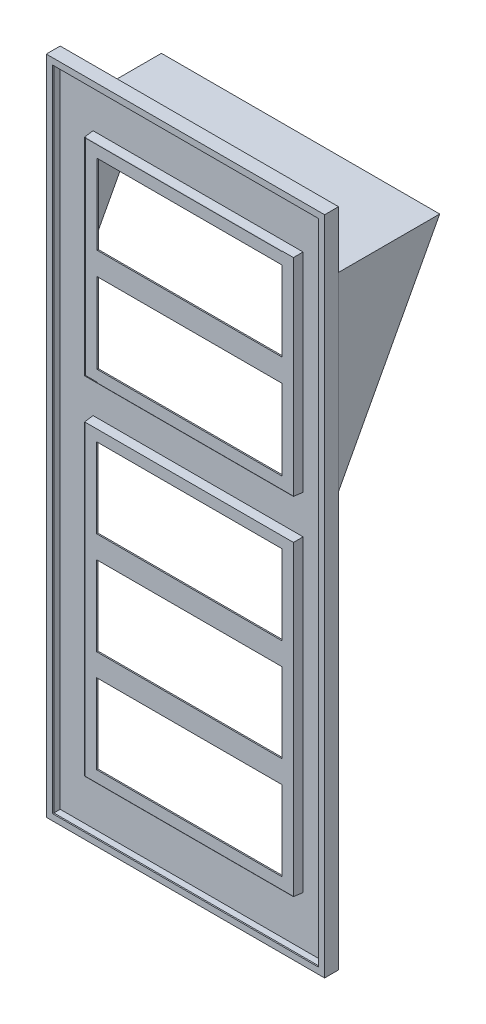
SolidWorks part; units mm, degrees
ref_plane "정면" through (0, 0, 0) normal (0, 0, 1) x (1, 0, 0)
ref_plane "윗면" through (0, 0, 0) normal (0, 1, 0) x (1, 0, 0)
ref_plane "우측면" through (0, 0, 0) normal (1, 0, 0) x (0, 0, -1)
sketch "스케치1" plane through (0, 0, 0) normal (0, 0, 1) x (1, 0, 0)
  line L1 (0, 0) -> (44, 0)
  line L2 (0, 0) -> (0, 104.5)
  line L3 (0, 104.5) -> (44, 104.5)
  line L4 (44, 0) -> (44, 104.5)
  dimension "D1" = 104.5
  dimension "D2" = 44
extrude "보스-돌출1" add sketch "스케치1" along normal blind 2
shell "쉘1" thickness 0.2
sketch "스케치2" plane through (0, 0, 0.2) normal (0, 0, 1) x (1, 0, 0)
  line L0 (44, 104.5) -> (0, 104.5) construction
  line L1 (5.6, 95.5) -> (38.4, 95.5)
  line L2 (5.6, 95.5) -> (5.6, 63)
  line L3 (5.6, 63) -> (38.4, 63)
  line L4 (38.4, 95.5) -> (38.4, 63)
  line L5 (5.6, 56.5) -> (38.4, 56.5)
  line L6 (5.6, 56.5) -> (5.6, 8.2)
  line L7 (5.6, 8.2) -> (38.4, 8.2)
  line L8 (38.4, 56.5) -> (38.4, 8.2)
  line L9 (0.2, 0.2) -> (43.8, 0.2) construction
  line L12 (0, 104.5) -> (0, 0) construction
  point P14 (22, 95.5)
  point P15 (22, 56.5)
  dimension "D1" = 9
  dimension "D2" = 32.5
  dimension "D3" = 6.5
  dimension "D4" = 8
  dimension "D5" = 32.8
  dimension "D6" = 32.8
  dimension "D7" = 22
  dimension "D8" = 22
extrude "컷-돌출1" cut sketch "스케치2" against normal blind 2
sketch "스케치3" plane through (0, 0, 0.2) normal (0, 0, 1) x (1, 0, 0)
  line L0 (5.6, 8.2) -> (38.4, 8.2) construction
  line L1 (5.6, 56.5) -> (5.6, 8.2) construction
  line L2 (38.4, 56.5) -> (5.6, 56.5) construction
  line L3 (38.4, 8.2) -> (38.4, 56.5) construction
  line L4 (5.6, 63) -> (38.4, 63)
  line L5 (5.6, 95.5) -> (5.6, 63)
  line L6 (38.4, 95.5) -> (5.6, 95.5)
  line L7 (38.4, 63) -> (38.4, 95.5)
  line L8 (5.6, 63) -> (38.4, 63)
  line L9 (5.6, 95.5) -> (5.6, 63)
  line L10 (38.4, 95.5) -> (5.6, 95.5)
  line L11 (38.4, 63) -> (38.4, 95.5)
  line L12 (5.6, 8.2) -> (38.4, 8.2)
  line L13 (5.6, 56.5) -> (5.6, 8.2)
  line L14 (38.4, 56.5) -> (5.6, 56.5)
  line L15 (38.4, 8.2) -> (38.4, 56.5)
  line L16 (5.4, 62.8) -> (38.6, 62.8)
  line L17 (38.6, 62.8) -> (38.6, 95.7)
  line L18 (38.6, 95.7) -> (5.4, 95.7)
  line L19 (5.4, 95.7) -> (5.4, 62.8)
  line L20 (5.4, 8) -> (38.6, 8)
  line L21 (38.6, 8) -> (38.6, 56.7)
  line L22 (38.6, 56.7) -> (5.4, 56.7)
  line L23 (5.4, 56.7) -> (5.4, 8)
  dimension "D1" = 0
  dimension "D2" = 0.2
extrude "보스-돌출2" add sketch "스케치3" along normal blind 1.8 draft 4
ref_plane "평면1" through (38.5, 95.6, 1.6301) normal (0, 1, 0) x (1, 0, 0)
ref_plane "평면2" through (0, 0, 1.4) normal (0, 0, 1) x (1, 0, 0)
sketch "스케치6" plane through (0, 0, 1.4) normal (0, 0, 1) x (1, 0, 0)
  line L0 (5.6, 63) -> (38.4, 63) construction
  line L1 (5.6, 95.5) -> (7.45, 95.5)
  line L2 (5.6, 95.5) -> (5.6, 63)
  line L3 (5.6, 63) -> (7.45, 63)
  line L4 (7.45, 95.5) -> (7.45, 63)
  line L6 (7.45, 64.75) -> (38.5, 64.75)
  line L7 (7.45, 64.75) -> (7.45, 62.9)
  line L8 (7.45, 62.9) -> (38.5, 62.9)
  line L9 (38.5, 64.75) -> (38.5, 62.9)
  line L11 (36.65, 64.75) -> (38.5, 64.75)
  line L12 (36.65, 64.75) -> (36.65, 95.6)
  line L13 (36.65, 95.6) -> (38.5, 95.6)
  line L14 (38.5, 64.75) -> (38.5, 95.6)
  line L15 (47.4925, 95.6) -> (29.5075, 95.6) construction
  line L16 (36.65, 93.65) -> (7.45, 93.65)
  line L17 (36.65, 93.65) -> (36.65, 95.5)
  line L18 (36.65, 95.5) -> (7.45, 95.5)
  line L19 (7.45, 93.65) -> (7.45, 95.5)
  line L20 (36.65, 77.45) -> (7.45, 77.45)
  line L21 (36.65, 77.45) -> (36.65, 81.05)
  line L22 (36.65, 81.05) -> (7.45, 81.05)
  line L23 (7.45, 77.45) -> (7.45, 81.05)
  line L24 (38.5, 62.9) -> (38.5, 95.6) construction
  dimension "D1" = 1.85
  dimension "D2" = 1.85
  dimension "D3" = 1.85
  dimension "D4" = 1.85
  dimension "D5" = 3.6
  dimension "D6" = 12.6
extrude "보스-돌출3" add sketch "스케치6" along normal blind 0.2 separate body contours L4 L1 L2 L3 | L9 L6 L4 L8 | L6 L14 L13 L12 | L12 L22 L4 L20 | L12 L18 L4 L16
sketch "스케치7" plane through (0, 0, 1.4) normal (0, 0, 1) x (1, 0, 0)
  line L1 (5.5, 56.6) -> (38.5, 56.6)
  line L2 (5.5, 56.6) -> (5.5, 8.1)
  line L3 (5.5, 8.1) -> (38.5, 8.1)
  line L4 (38.5, 56.6) -> (38.5, 8.1)
  line L5 (7.35, 22.5) -> (36.65, 22.5)
  line L6 (7.35, 22.5) -> (7.35, 9.9)
  line L7 (7.35, 9.9) -> (36.65, 9.9)
  line L8 (36.65, 22.5) -> (36.65, 9.9)
  line L9 (7.35, 38.65) -> (36.65, 38.65)
  line L10 (7.35, 38.65) -> (7.35, 26.05)
  line L11 (7.35, 26.05) -> (36.65, 26.05)
  line L12 (36.65, 38.65) -> (36.65, 26.05)
  line L13 (7.35, 54.8) -> (36.65, 54.8)
  line L14 (7.35, 54.8) -> (7.35, 42.2)
  line L15 (7.35, 42.2) -> (36.65, 42.2)
  line L16 (36.65, 54.8) -> (36.65, 42.2)
  dimension "D1" = 1.8
  dimension "D2" = 3.55
  dimension "D3" = 3.55
  dimension "D4" = 12.6
  dimension "D5" = 1.85
  dimension "D6" = 1.85
  dimension "D7" = 1.85
  dimension "D8" = 1.85
extrude "보스-돌출4" add sketch "스케치7" along normal blind 0.2
sketch "스케치11" plane through (0, 0, 0) normal (-1, 0, 0) x (0, 0, 1)
  line L0 (0, 95.5) -> (-16, 95.5)
  line L1 (0, 104.5) -> (0, 0) construction
  line L2 (-16, 95.5) -> (0, 65.5)
  line L3 (2, 104.5) -> (0, 104.5) construction
  line L4 (0, 95.5) -> (0, 65.5)
  dimension "D1" = 9
  dimension "D2" = 16
  dimension "D3" = 30
extrude "보스-돌출6" add sketch "스케치11" against normal blind 44 separate body
sketch "스케치12" plane through (0, 0, 0) normal (0, 0, -1) x (-1, 0, 0)
  line L36 (-0.2, 95.3) -> (-43.8, 95.3)
  line L37 (-43.8, 95.3) -> (-43.8, 65.5)
  line L38 (-43.8, 65.5) -> (-0.2, 65.5)
  line L39 (-0.2, 65.5) -> (-0.2, 95.3)
  line L48 (-5.6, 95.5) -> (-38.4, 95.5) construction
  line L49 (0, 95.5) -> (0, 65.5) construction
  line L51 (-44, 95.5) -> (-44, 65.5) construction
  line L52 (-44, 65.5) -> (0, 65.5) construction
  dimension "D1" = 0.2
  dimension "D2" = 0.2
  dimension "D4" = 0.2
extrude "컷-돌출5" cut sketch "스케치12" along normal blind 16
sketch "스케치13" plane through (0, 0, 2) normal (0, 0, 1) x (1, 0, 0)
  line L0 (43, 103.5) -> (43, 1)
  line L1 (44, 104.5) -> (0, 104.5)
  line L2 (44, 104.5) -> (44, 0)
  line L3 (44, 0) -> (0, 0)
  line L4 (0, 104.5) -> (0, 0)
  line L5 (43, 1) -> (1, 1)
  line L6 (1, 103.5) -> (1, 1)
  line L7 (43, 103.5) -> (1, 103.5)
  dimension "D1" = 1
extrude "보스-돌출7" add sketch "스케치13" along normal blind 0.2
